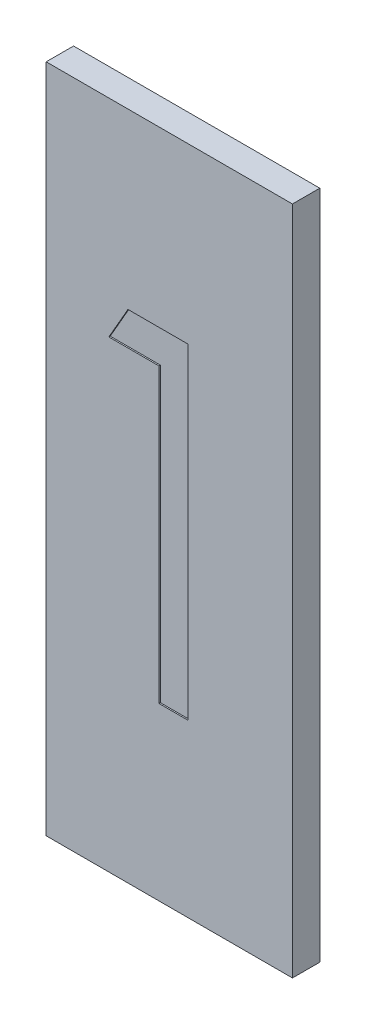
SolidWorks part; units mm, degrees
ref_plane "正面" through (0, 0, 0) normal (0, 0, 1) x (1, 0, 0)
ref_plane "平面" through (0, 0, 0) normal (0, 1, 0) x (1, 0, 0)
ref_plane "右側面" through (0, 0, 0) normal (1, 0, 0) x (0, 0, -1)
sketch "ｽｹｯﾁ1" plane through (0, 0, 0) normal (0, 0, 1) x (1, 0, 0)
  line L0 (18, 0) -> (0, 0)
  line L1 (18, 49) -> (0, 49)
  line L2 (0, 0) -> (0, 49)
  line L4 (18, 0) -> (18, 49)
extrude "ﾎﾞｽ - 押し出し1" add sketch "ｽｹｯﾁ1" along normal blind 2
sketch "ｽｹｯﾁ2" plane through (0, 0, 2) normal (0, 0, 1) x (1, 0, 0)
  text T0 "1" font "Century Gothic" height in points 90
extrude "ｶｯﾄ - 押し出し1" cut sketch "ｽｹｯﾁ2" against normal blind 0.1
